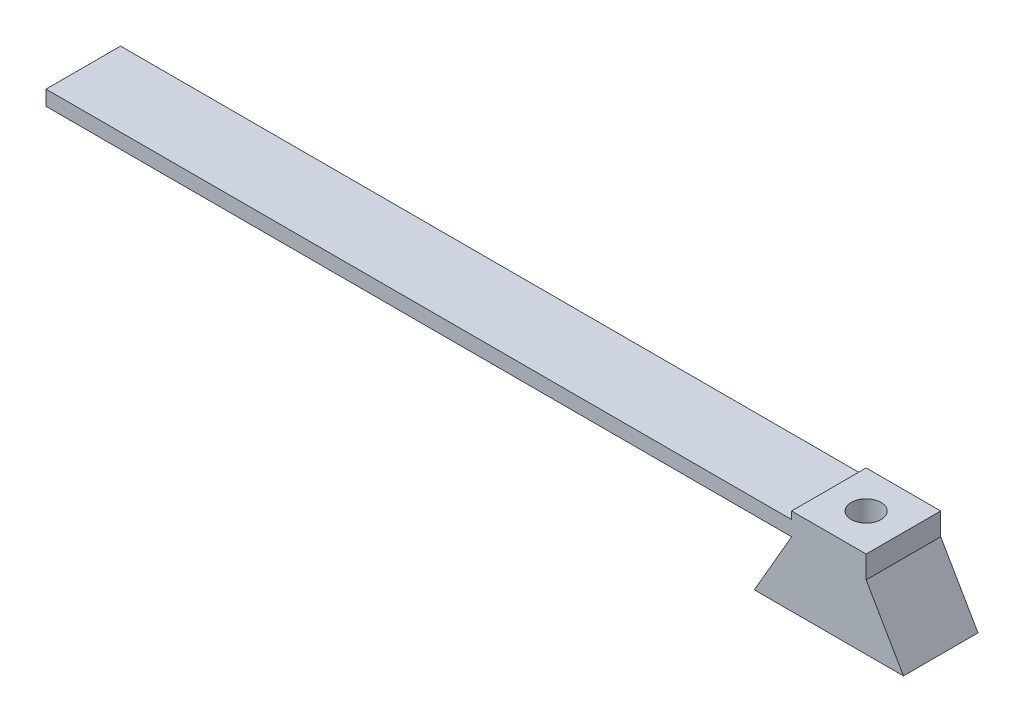
SolidWorks part; units mm, degrees
ref_plane "Alzado" through (0, 0, 0) normal (0, 0, 1) x (1, 0, 0)
ref_plane "Planta" through (0, 0, 0) normal (0, 1, 0) x (1, 0, 0)
ref_plane "Vista lateral" through (0, 0, 0) normal (1, 0, 0) x (0, 0, -1)
sketch "Croquis1" plane through (0, 0, 0) normal (0, 0, 1) x (1, 0, 0)
  line L0 (0, 0) -> (50, 86.6025)
  line L1 (50, 86.6025) -> (150, 86.6025)
  line L2 (150, 86.6025) -> (200, 0)
  line L3 (200, 0) -> (0, 0)
  dimension "D1" = 200
  dimension "D2" = 100
  dimension "D3" = 60
  dimension "D4" = 60
extrude "Saliente-Extruir1" add sketch "Croquis1" along normal blind 100
sketch "Croquis2" plane through (0, 86.6025, 0) normal (0, 1, 0) x (1, 0, 0)
  line L0 (150, -100) -> (150, 0) construction
  line L1 (50, 0) -> (150, 0)
  line L2 (50, 0) -> (50, -100)
  line L3 (50, -100) -> (150, -100)
  line L4 (150, 0) -> (150, -100)
extrude "Saliente-Extruir2" add sketch "Croquis2" along normal blind 20
sketch "Croquis3" plane through (50, 0, 0) normal (-1, 0, 0) x (0, 0, 1)
  line L1 (0, 106.6025) -> (100, 106.6025)
  line L2 (0, 106.6025) -> (0, 86.6025)
  line L3 (0, 86.6025) -> (100, 86.6025)
  line L4 (100, 106.6025) -> (100, 86.6025)
extrude "Saliente-Extruir3" add sketch "Croquis3" along normal blind 1000
sketch "Croquis4" plane through (0, 106.6025, 0) normal (0, 1, 0) x (1, 0, 0)
  line L2 (0, 0) -> (200, 0) construction
  line L4 (150, -100) -> (150, 0) construction
  line L5 (-950, -100) -> (150, -100) construction
  line L6 (150, 0) -> (50, 0)
  line L7 (150, 0) -> (150, -100)
  line L8 (150, -100) -> (50, -100)
  line L9 (50, 0) -> (50, -100)
  circle A1 centre (100, -50) radius 20
  point P5 (100, 0)
  point P7 (0, 0)
  point P10 (150, -50)
  point P16 (50, -50)
  dimension "D1" = 40
  dimension "D2" = 100
  dimension "D3" = 100
extrude "Saliente-Extruir4" add sketch "Croquis4" along normal blind 10
sketch "Croquis7" plane through (0, 116.6025, 0) normal (0, 1, 0) x (1, 0, 0)
  circle A0 centre (100, -50) radius 20
extrude "Cortar-Extruir2" cut sketch "Croquis7" against normal mid plane 457
